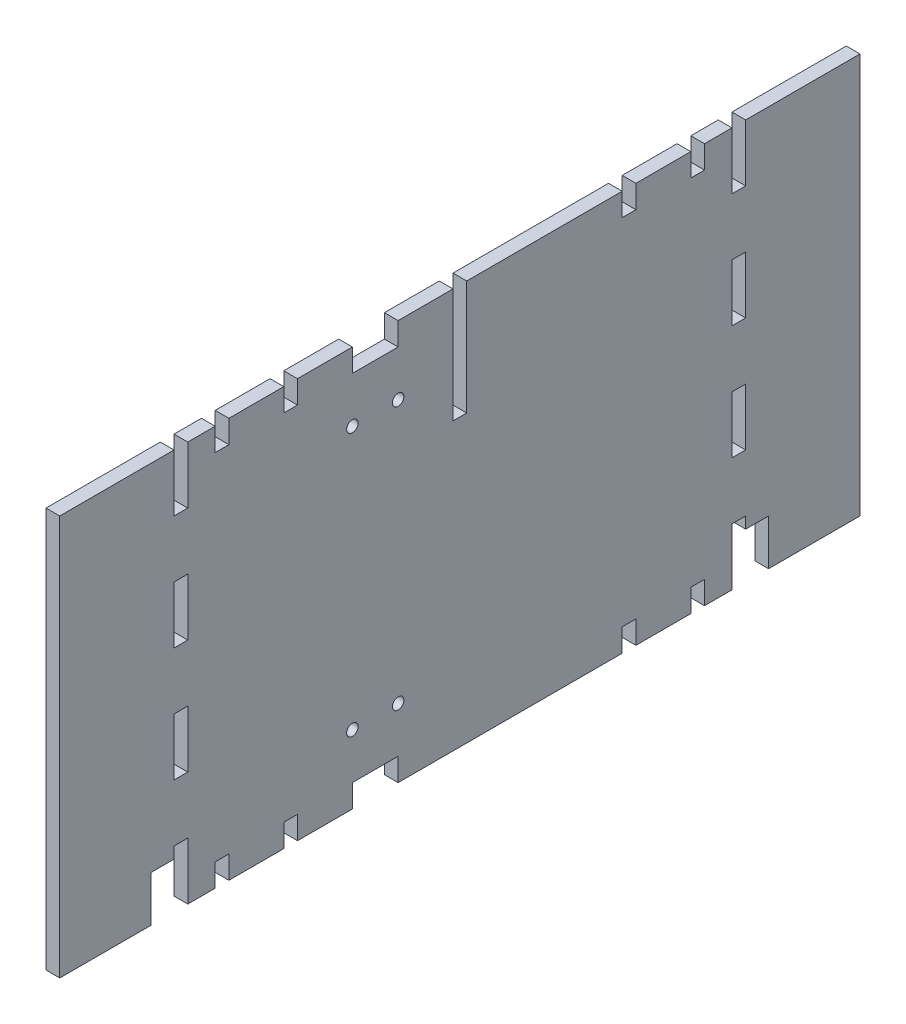
SolidWorks part; units mm, degrees
ref_plane "Front" through (0, 0, 0) normal (0, 0, 1) x (1, 0, 0)
ref_plane "Top" through (0, 0, 0) normal (0, 1, 0) x (1, 0, 0)
ref_plane "Right" through (0, 0, 0) normal (1, 0, 0) x (0, 0, -1)
sketch "Sketch1" plane through (0, 0, 0) normal (1, 0, 0) x (0, 0, -1)
  line L1 (0, 0) -> (-350, 0)
  line L2 (0, 0) -> (0, 175)
  line L3 (0, 175) -> (-350, 175)
  line L4 (-350, 0) -> (-350, 175)
  dimension "D1" = 350
  dimension "D2" = 175
extrude "Boss-Extrude1" add sketch "Sketch1" along normal blind 6
ref_plane "Plane1" through (0, 0, 175) normal (0, 0, 1) x (1, 0, 0)
sketch "Sketch3" plane through (6, 0, 0) normal (1, 0, 0) x (0, 0, -1)
  line L0 (-350, 175) -> (-350, 0) construction
  line L1 (-300, 175) -> (-294, 175)
  line L2 (-300, 175) -> (-300, 150)
  line L3 (-300, 150) -> (-294, 150)
  line L4 (-294, 175) -> (-294, 150)
  line L5 (0, 175) -> (-350, 175) construction
  dimension "D1" = 6
  dimension "D2" = 25
  dimension "D3" = 50
extrude "Cut-Extrude1" cut sketch "Sketch3" against normal through all
pattern_linear "LPattern1" count 4 spacing 50 along (0, -1, 0) of "Cut-Extrude1"
sketch "Sketch4" plane through (6, 0, 0) normal (1, 0, 0) x (0, 0, -1)
  line L0 (0, 175) -> (-294, 175) construction
  line L1 (-282, 175) -> (-276, 175)
  line L2 (-282, 175) -> (-282, 165)
  line L3 (-282, 165) -> (-276, 165)
  line L4 (-276, 175) -> (-276, 165)
  line L5 (-294, 150) -> (-294, 175) construction
  dimension "D1" = 6
  dimension "D2" = 12
  dimension "D3" = 10
extrude "Cut-Extrude2" cut sketch "Sketch4" against normal through all
pattern_linear "LPattern2" count 2 spacing 165 along (0, -1, 0) of "Cut-Extrude2"
sketch "Sketch5" plane through (6, 0, 0) normal (1, 0, 0) x (0, 0, -1)
  line L0 (0, 175) -> (-276, 175) construction
  line L1 (-252, 175) -> (-246, 175)
  line L2 (-252, 175) -> (-252, 165)
  line L3 (-252, 165) -> (-246, 165)
  line L4 (-246, 175) -> (-246, 165)
  line L5 (-276, 165) -> (-276, 175) construction
  line L6 (-282, 165) -> (-276, 165) construction
  dimension "D1" = 24
  dimension "D2" = 6
extrude "Cut-Extrude3" cut sketch "Sketch5" against normal through all
pattern_linear "LPattern3" count 2 spacing 165 along (0, -1, 0) of "Cut-Extrude3"
sketch "Sketch6" plane through (6, 0, 0) normal (1, 0, 0) x (0, 0, -1)
  line L0 (0, 175) -> (-246, 175) construction
  line L1 (-178, 175) -> (-172, 175)
  line L2 (-178, 175) -> (-178, 125)
  line L3 (-178, 125) -> (-172, 125)
  line L4 (-172, 175) -> (-172, 125)
  line L5 (-175, 3.3) -> (-175, -3.3) construction
  point P6 (-175, 175)
  dimension "D1" = 6
  dimension "D2" = 50
extrude "Cut-Extrude4" cut sketch "Sketch6" against normal blind 10
sketch "Sketch7" plane through (6, 0, 0) normal (1, 0, 0) x (0, 0, -1)
  line L0 (-178, 175) -> (-246, 175) construction
  line L1 (-222, 175) -> (-202, 175)
  line L2 (-222, 175) -> (-222, 165)
  line L3 (-222, 165) -> (-202, 165)
  line L4 (-202, 175) -> (-202, 165)
  point P6 (-212, 175)
  point P7 (-212, 175)
  dimension "D1" = 10
  dimension "D2" = 20
extrude "Cut-Extrude5" cut sketch "Sketch7" against normal blind 10
pattern_linear "LPattern4" count 2 spacing 165 along (0, -1, 0) of "Cut-Extrude5"
sketch "Sketch8" plane through (6, 0, 0) normal (1, 0, 0) x (0, 0, -1)
  line L0 (-222, 145) -> (-202, 145) construction
  line L1 (-222, 30) -> (-202, 30) construction
  line L2 (-212, 165) -> (-212, 10) construction
  line L3 (-222, 165) -> (-202, 165) construction
  line L4 (-202, 10) -> (-222, 10) construction
  circle A0 centre (-222, 145) radius 2.5
  circle A1 centre (-202, 145) radius 2.5
  circle A2 centre (-222, 30) radius 2.5
  circle A3 centre (-202, 30) radius 2.5
  point P8 (-212, 145)
  point P15 (-212, 30)
  dimension "D3" = 5
  dimension "D1" = 20
  dimension "D2" = 20
  dimension "D4" = 20
extrude "Cut-Extrude6" cut sketch "Sketch8" against normal blind 10
sketch "Sketch9" plane through (6, 0, 0) normal (1, 0, 0) x (0, 0, -1)
  line L1 (-300, 20) -> (-310, 20)
  line L2 (-300, 20) -> (-300, 0)
  line L3 (-300, 0) -> (-310, 0)
  line L4 (-310, 20) -> (-310, 0)
  line L5 (-350, 0) -> (-300, 0) construction
  line L6 (-300, 25) -> (-300, 0) construction
  point P4 (-300, 20)
  dimension "D1" = 10
  dimension "D2" = 20
extrude "Cut-Extrude7" cut sketch "Sketch9" against normal blind 10
mirror "Mirror1" about plane through (0, 0, 175) normal (0, 0, 1) of "LPattern3", "LPattern2", "LPattern1", "Cut-Extrude7", "Cut-Extrude1", "Cut-Extrude2", "Cut-Extrude3"
equation "\"`10\"=11.8105"
